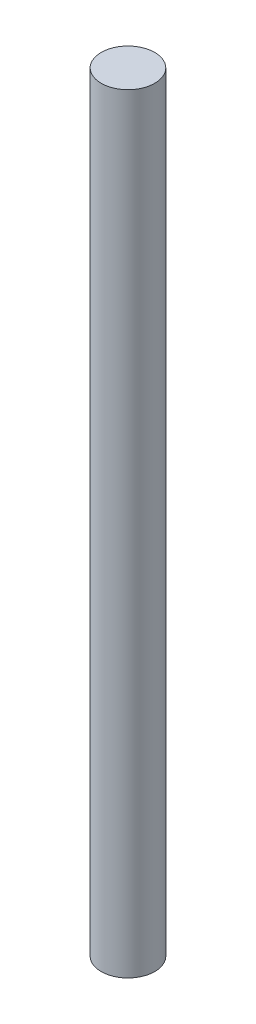
SolidWorks part; units mm, degrees
ref_plane "Front Plane" through (0, 0, 0) normal (0, 0, 1) x (1, 0, 0)
ref_plane "Top Plane" through (0, 0, 0) normal (0, 1, 0) x (1, 0, 0)
ref_plane "Right Plane" through (0, 0, 0) normal (1, 0, 0) x (0, 0, -1)
sketch "Sketch1" plane through (0, 0, 0) normal (0, 1, 0) x (1, 0, 0)
  circle A0 centre (0, 0) radius 4
  dimension "D1" = 8
extrude "Boss-Extrude1" add sketch "Sketch1" along normal blind 115
